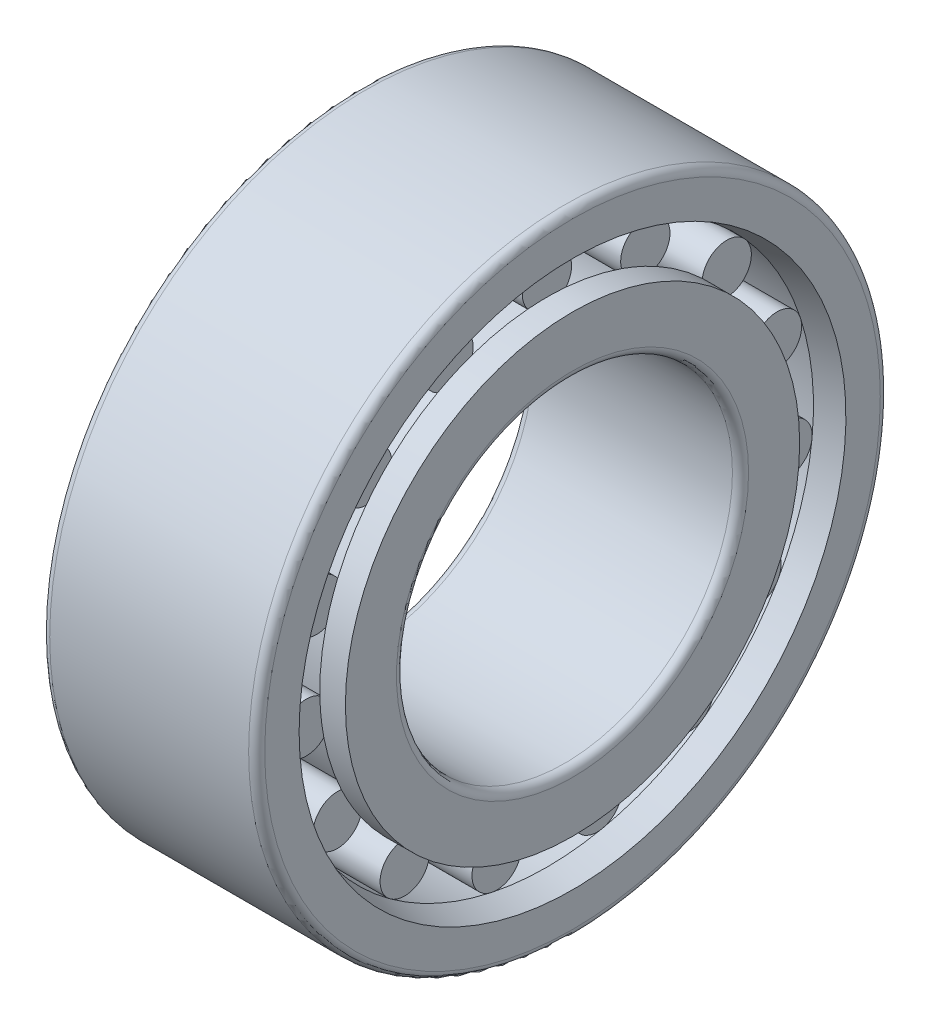
SolidWorks part; units mm, degrees
material "GCr4"
ref_plane "前视" through (0, 0, 0) normal (0, 0, 1) x (1, 0, 0)
ref_plane "上视" through (0, 0, 0) normal (0, 1, 0) x (1, 0, 0)
ref_plane "右视" through (0, 0, 0) normal (1, 0, 0) x (0, 0, -1)
sketch "尺寸草图" plane through (0, 0, 0) normal (0, 0, 1) x (1, 0, 0)
  line L0 (0, 0) -> (47, 0)
  point P3 (25, 0)
  point P4 (16, 0)
  point P5 (0.6, 0)
  dimension "DD" = 47
  dimension "d" = 25
  dimension "B" = 16
  dimension "r" = 0.6
sketch "草图1" plane through (0, 0, 0) normal (0, 0, 1) x (1, 0, 0)
  line L0 (0, 0) -> (0, 110.1282) construction
  line L1 (0, 0) -> (226.5796, 0) construction
  line L2 (0.6, 23.5) -> (15.4, 23.5)
  line L3 (16, 13.1) -> (16, 16.9) construction
  line L4 (0.6, 12.5) -> (15.4, 12.5) construction
  line L5 (0, 22.9) -> (0, 20.3437)
  line L6 (-94.0488, 18) -> (162.4539, 18) construction
  line L7 (1.9048, 19.8333) -> (14.0952, 19.8333)
  line L8 (1.9048, 16.1667) -> (6.4762, 16.1667) construction
  line L9 (6.4762, 19.8333) -> (6.4762, 16.1667) construction
  line L10 (9.5238, 16.1667) -> (9.5238, 19.8333) construction
  line L11 (14.0952, 16.1667) -> (14.0952, 19.8333) construction
  line L12 (1.9048, 19.8333) -> (1.9048, 16.1667) construction
  line L13 (8, 23.5) -> (8, 12.5) construction
  line L14 (0, 16.9) -> (0, 13.1) construction
  line L15 (16, 20.3437) -> (16, 22.9)
  line L16 (0, 16.9) -> (1.9048, 16.9) construction
  line L17 (6.4762, 16.9) -> (9.5238, 16.9) construction
  line L18 (14.0952, 16.9) -> (16, 16.9) construction
  line L19 (9.5238, 16.1667) -> (14.0952, 16.1667) construction
  line L20 (0, 20.3437) -> (1.9048, 19.8333)
  line L21 (14.0952, 19.8333) -> (16, 20.3437)
  arc A0 (0.6, 23.5) -> (0, 22.9) centre (0.6, 22.9) ccw
  arc A1 (15.4, 23.5) -> (16, 22.9) centre (15.4, 22.9) cw
  arc A2 (0.6, 12.5) -> (0, 13.1) centre (0.6, 13.1) cw construction
  arc A3 (15.4, 12.5) -> (16, 13.1) centre (15.4, 13.1) ccw construction
  point P15 (0, 19.8333)
  point P16 (16, 19.8333)
  point P30 (0, 23.5)
  point P33 (16, 23.5)
  dimension "D8" = 0.6
  dimension "D4" = 12.1905
  dimension "D5" = 3.0476
  dimension "D6" = 3.6667
  dimension "D2" = 16
  dimension "D9" = 1.9048
  dimension "D10" = 15
  dimension "D11" = 1.9048
  dimension "D12" = 15
  dimension "D3" = 47
  dimension "D13" = 12.5
  dimension "D7" = 0.7333
revolve "基体-旋转" add sketch "草图1" angle 360 about L1
sketch "草图4" plane through (0, 0, 0) normal (0, 0, 1) x (1, 0, 0)
  line L0 (1.9048, 18) -> (6.4762, 18)
  line L1 (1.9048, 19.8333) -> (14.0952, 19.8333) construction
  line L2 (6.4762, 19.8333) -> (6.4762, 16.1667) construction
  line L3 (-94.0488, 18) -> (162.4539, 18) construction
  line L4 (1.9048, 19.8333) -> (1.9048, 16.1667) construction
  line L5 (1.9048, 19.8343) -> (6.4762, 19.8343)
  line L6 (1.9048, 19.8333) -> (6.4762, 19.8333) construction
  line L7 (6.4762, 19.8343) -> (6.4762, 18)
  line L8 (-94.0488, 18) -> (162.4539, 18) construction
  line L9 (1.9048, 19.8343) -> (1.9048, 18)
  dimension "D1" = 0.001
revolve "凸台-旋转1" add sketch "草图4" angle 360 about L8
sketch "草图5" plane through (0, 0, 0) normal (0, 0, 1) x (1, 0, 0)
  line L0 (1.9048, 19.8333) -> (14.0952, 19.8333) construction
  line L1 (-94.0488, 18) -> (162.4539, 18) construction
  line L2 (14.0952, 16.1667) -> (14.0952, 19.8333) construction
  line L3 (9.5238, 16.1667) -> (9.5238, 19.8333) construction
  line L4 (9.5238, 19.8333) -> (14.0952, 19.8333) construction
  line L5 (-94.0488, 18) -> (162.4539, 18) construction
  line L6 (14.0952, 18) -> (14.0952, 19.8343)
  line L7 (9.5238, 18) -> (9.5238, 19.8343)
  line L8 (9.5238, 19.8343) -> (14.0952, 19.8343)
  line L9 (9.5238, 18) -> (14.0952, 18)
  dimension "D1" = 0.001
revolve "凸台-旋转2" add sketch "草图5" angle 360 about L5
sketch "草图2" plane through (0, 0, 0) normal (0, 0, 1) x (1, 0, 0)
  line L0 (14.0952, 16.1667) -> (14.0952, 19.8333) construction
  line L1 (6.4762, 19.8333) -> (6.4762, 16.1667) construction
  line L2 (14.0952, 16.9) -> (16, 16.9) construction
  line L3 (6.4762, 16.9) -> (9.5238, 16.9) construction
  line L4 (0.6, 12.5) -> (15.4, 12.5) construction
  line L5 (16, 13.1) -> (16, 16.9) construction
  line L6 (9.5238, 16.1667) -> (14.0952, 16.1667) construction
  line L7 (0, 16.9) -> (0, 13.1) construction
  line L8 (0, 16.9) -> (1.9048, 16.9) construction
  line L9 (1.9048, 16.1667) -> (6.4762, 16.1667) construction
  line L10 (14.0952, 16.1667) -> (14.0952, 16.9)
  line L11 (6.4762, 16.9) -> (6.4762, 16.1667)
  line L12 (14.0952, 16.9) -> (16, 16.9)
  line L13 (6.4762, 16.9) -> (9.5238, 16.9)
  line L14 (0.6, 12.5) -> (15.4, 12.5)
  line L15 (16, 13.1) -> (16, 16.9)
  line L16 (9.5238, 16.1667) -> (14.0952, 16.1667)
  line L17 (0, 16.9) -> (0, 13.1)
  line L18 (0, 16.9) -> (1.9048, 16.9)
  line L19 (1.9048, 16.1667) -> (6.4762, 16.1667)
  line L20 (9.5238, 16.1667) -> (9.5238, 19.8333) construction
  line L21 (1.9048, 19.8333) -> (1.9048, 16.1667) construction
  line L22 (9.5238, 16.1667) -> (9.5238, 16.9)
  line L23 (1.9048, 16.9) -> (1.9048, 16.1667)
  line L26 (0, 0) -> (-135.6746, 0) construction
  arc A0 (15.4, 12.5) -> (16, 13.1) centre (15.4, 13.1) ccw construction
  arc A1 (0, 13.1) -> (0.6, 12.5) centre (0.6, 13.1) ccw construction
  arc A2 (15.4, 12.5) -> (16, 13.1) centre (15.4, 13.1) ccw
  arc A3 (0, 13.1) -> (0.6, 12.5) centre (0.6, 13.1) ccw
revolve "凸台-旋转3" add sketch "草图2" angle 360 about L26
pattern_circular "阵列(圆周)1" count 15 over 360 about axis through (0, 0, 0) along (1, 0, 0) of "凸台-旋转2", "凸台-旋转1"
equation "\"D8@草图1\" = \"r@尺寸草图\""
equation "\"D2@草图1\"= \"B@尺寸草图\" "
equation "\"D13@草图1\" = \"d@尺寸草图\"/ 2"
equation "\"D3@草图1\" = \"DD@尺寸草图\""
equation "\"D6@草图1\" =  ( \"D3@草图1\" - \"D13@草图1\" * 2 )  / 6"
equation "\"D7@草图1\" = \"D6@草图1\" / 5"
equation "\"D4@草图1\" = \"D2@草图1\" / 3.5 * 8 / 3"
equation "\"D9@草图1\" = (  \"D2@草图1\" - \"D4@草图1\" ) / 2"
equation "\"D11@草图1\" = \"D9@草图1\""
equation "\"D5@草图1\" = \"D2@草图1\" / 3.5 * 2 / 3"
equation "\"D1@阵列(圆周)1\" = 3.14 *  ( \"D3@草图1\" + \"D13@草图1\" * 2 ) /4 / \"D6@草图1\""
